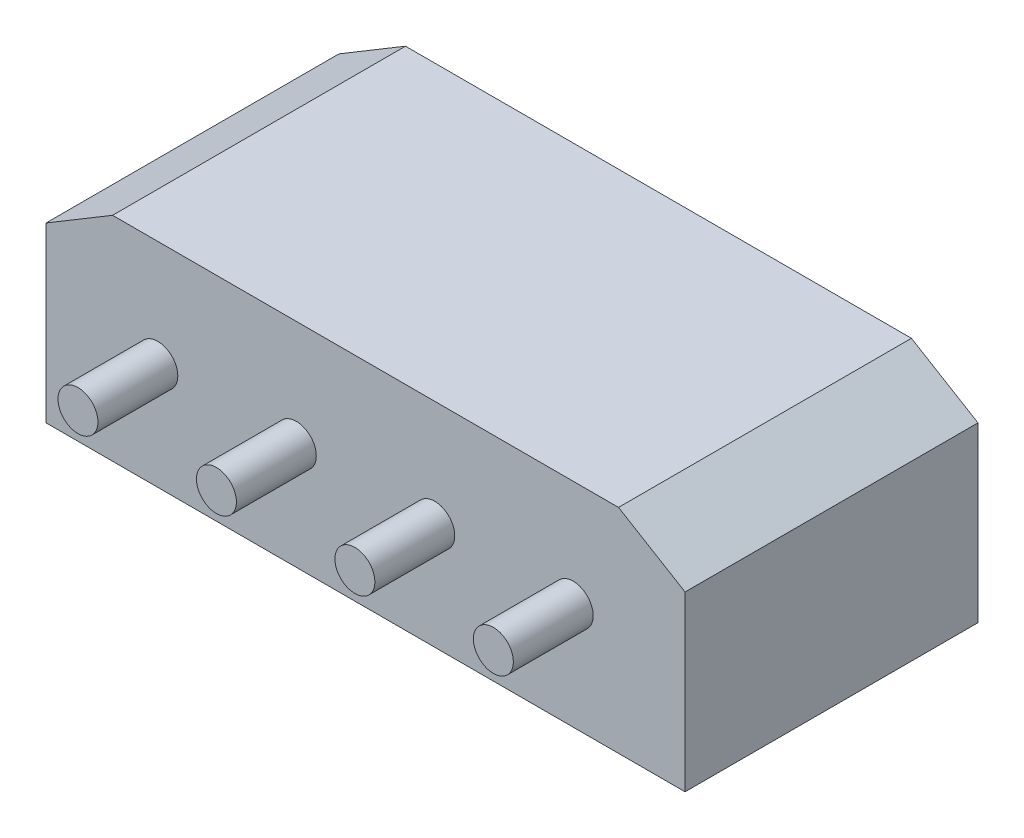
SolidWorks part; units mm, degrees
ref_plane "前视基准面" through (0, 0, 0) normal (0, 0, 1) x (1, 0, 0)
ref_plane "上视基准面" through (0, 0, 0) normal (0, 1, 0) x (1, 0, 0)
ref_plane "右视基准面" through (0, 0, 0) normal (1, 0, 0) x (0, 0, -1)
sketch "草图1" plane through (0, 0, 0) normal (0, 0, 1) x (1, 0, 0)
  line L0 (2.9233, 6.5) -> (-39.4264, 6.5) construction
  line L1 (0, 0) -> (-24, 0)
  line L2 (0, 0) -> (0, 6.5)
  line L3 (-2.5, 8) -> (-21.5, 8)
  line L4 (-2.5, 8) -> (0, 6.5)
  line L5 (-12, 0) -> (-12, 9.0649) construction
  line L6 (-24, 0) -> (-24, 6.5)
  line L7 (-21.5, 8) -> (-24, 6.5)
  point P9 (-12, 8)
  dimension "D1" = 24
  dimension "D2" = 8
  dimension "D3" = 6.5
extrude "凸台-拉伸1" add sketch "草图1" along normal blind 11
sketch "草图2" plane through (0, 0, 0) normal (0, 0, -1) x (-1, 0, 0)
  line L18 (1, 5.9338) -> (1, 1)
  line L19 (1, 1) -> (23, 1)
  line L20 (23, 1) -> (23, 5.9338)
  line L21 (23, 5.9338) -> (21.223, 7)
  line L22 (21.223, 7) -> (2.777, 7)
  line L23 (2.777, 7) -> (1, 5.9338)
  line L24 (1, 5.9338) -> (1, 1)
  line L25 (1, 1) -> (23, 1)
  line L26 (23, 1) -> (23, 5.9338)
  line L27 (23, 5.9338) -> (21.223, 7)
  line L28 (21.223, 7) -> (2.777, 7)
  line L29 (2.777, 7) -> (1, 5.9338)
  dimension "D1" = 1
extrude "切除-拉伸1" cut sketch "草图2" against normal blind 9
sketch "草图3" plane through (0, 0, 9) normal (0, 0, -1) x (-1, 0, 0)
  line L0 (2.5, 8) -> (2.5, 0) construction
  line L1 (24, 0) -> (0, 0) construction
  line L2 (2.5, 4) -> (30.9492, 4) construction
  line L3 (12, 0) -> (12, 10.1085) construction
  circle A0 centre (4.2, 4) radius 0.75
  dimension "D1" = 1.5
  dimension "D2" = 15.6
extrude "凸台-拉伸2" add sketch "草图3" along normal mid plane 18
sketch "草图4" plane through (0, 0, 18) normal (0, 0, 1) x (1, 0, 0)
  circle A0 centre (-4.2, 4) radius 1.7731
extrude "切除-拉伸2" cut sketch "草图4" against normal blind 4
pattern_linear "阵列(线性)1" count 4 spacing 5.2 along (-1, 0, 0) of "切除-拉伸2", "凸台-拉伸2"
